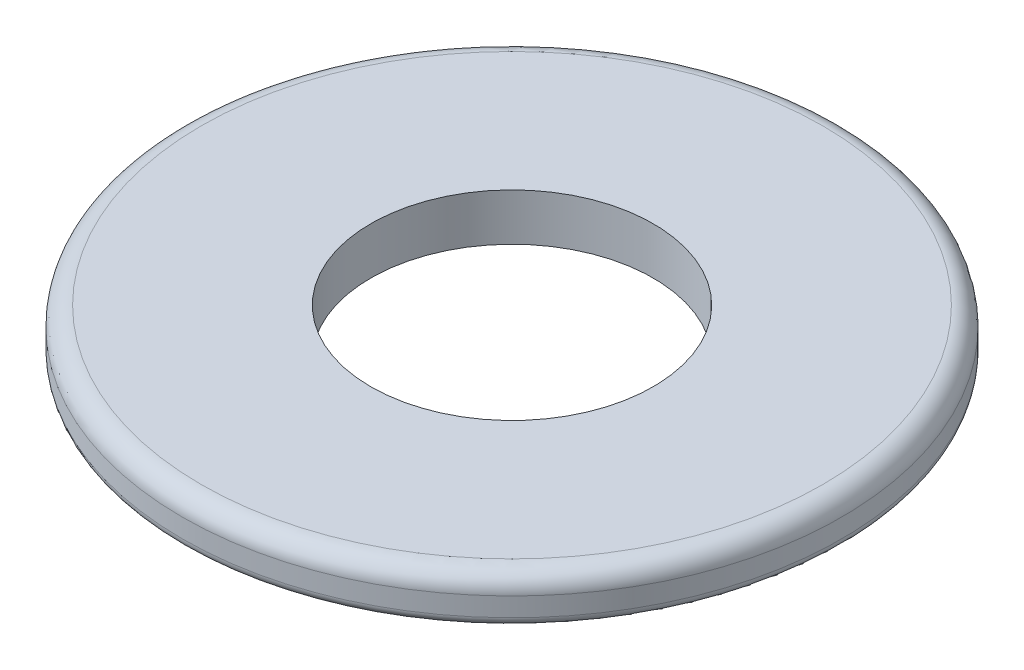
SolidWorks part; units mm, degrees
ref_plane "Front Plane" through (0, 0, 0) normal (0, 0, 1) x (1, 0, 0)
ref_plane "Top Plane" through (0, 0, 0) normal (0, 1, 0) x (1, 0, 0)
ref_plane "Right Plane" through (0, 0, 0) normal (1, 0, 0) x (0, 0, -1)
sketch "Sketch1" plane through (0, 0, 0) normal (0, 1, 0) x (1, 0, 0)
  circle A0 centre (0, 0) radius 1.5
  circle A1 centre (0, 0) radius 3.5
  dimension "D1" = 3
  dimension "D2" = 7
extrude "Boss-Extrude1" add sketch "Sketch1" along normal blind 0.5
fillet "Fillet1" radius 0.2 1 edges at (0, 0.5, 3.5)
fillet "Fillet2" radius 0.1 1 edges at (0, 0, 3.5)
